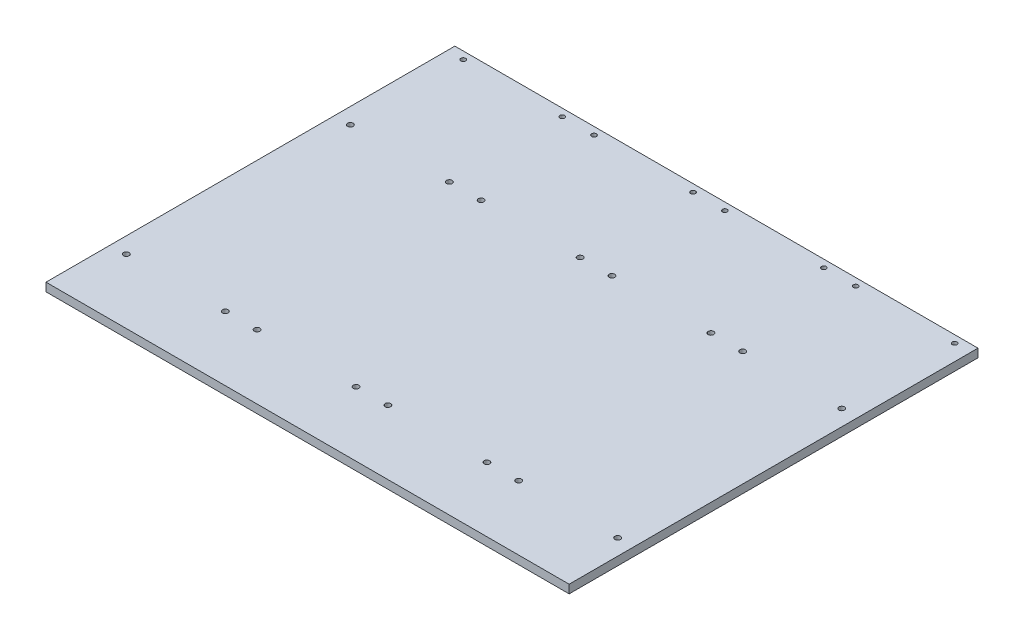
SolidWorks part; units mm, degrees
ref_plane "Front Plane" through (0, 0, 0) normal (0, 0, 1) x (1, 0, 0)
ref_plane "Top Plane" through (0, 0, 0) normal (0, 1, 0) x (1, 0, 0)
ref_plane "Right Plane" through (0, 0, 0) normal (1, 0, 0) x (0, 0, -1)
sketch "Sketch1" plane through (0, 0, 0) normal (0, 1, 0) x (1, 0, 0)
  line L0 (-23.35, 0) -> (23.35, 0) construction
  line L1 (-23.35, 72.9977) -> (23.35, 72.9977)
  line L2 (-23.35, 72.9977) -> (-23.35, -72.9977)
  line L3 (-23.35, -72.9977) -> (23.35, -72.9977)
  line L4 (23.35, 72.9977) -> (23.35, -72.9977)
  line L5 (-23.35, 72.9977) -> (23.35, -72.9977) construction
  line L6 (-23.35, -72.9977) -> (23.35, 72.9977) construction
  line L7 (0, 72.9977) -> (0, -72.9977) construction
  line L8 (-17.675, 72.9977) -> (-17.675, -72.9977) construction
  line L9 (-20.35, 72.9977) -> (-20.35, -72.9977) construction
  line L10 (-15, 72.9977) -> (-15, -72.9977) construction
  line L11 (20.35, 72.9977) -> (20.35, -72.9977) construction
  line L12 (17.675, 72.9977) -> (17.675, -72.9977) construction
  line L13 (15, 72.9977) -> (15, -72.9977) construction
  line L15 (23.35, 72.9977) -> (23.35, -72.9977)
  line L18 (23.35, 72.9977) -> (70.05, 72.9977)
  line L19 (23.35, 72.9977) -> (23.35, -72.9977)
  line L20 (23.35, -72.9977) -> (70.05, -72.9977)
  line L21 (70.05, 72.9977) -> (70.05, -72.9977)
  line L22 (70.05, 72.9977) -> (70.05, -72.9977)
  line L23 (23.35, 0) -> (70.05, 0) construction
  line L24 (23.35, 72.9977) -> (70.05, -72.9977) construction
  line L25 (23.35, -72.9977) -> (70.05, 72.9977) construction
  line L26 (46.7, 72.9977) -> (46.7, -72.9977) construction
  line L27 (29.025, 72.9977) -> (29.025, -72.9977) construction
  line L32 (26.35, 72.9977) -> (26.35, -72.9977) construction
  line L33 (31.7, 72.9977) -> (31.7, -72.9977) construction
  line L34 (67.05, 72.9977) -> (67.05, -72.9977) construction
  line L35 (64.375, 72.9977) -> (64.375, -72.9977) construction
  line L36 (61.7, 72.9977) -> (61.7, -72.9977) construction
  line L37 (23.35, -69.9977) -> (70.05, -69.9977) construction
  line L38 (23.35, 50.0023) -> (70.05, 50.0023) construction
  line L39 (23.35, 52.9977) -> (70.05, 52.9977) construction
  line L40 (26.35, 67.6477) -> (31.7, 67.6477) construction
  line L41 (23.35, 50.0023) -> (23.35, -69.9977) construction
  line L46 (23.35, -9.9977) -> (70.05, -9.9977) construction
  line L47 (70.05, 72.9977) -> (116.75, 72.9977)
  line L48 (70.05, 72.9977) -> (70.05, -72.9977)
  line L49 (70.05, -72.9977) -> (116.75, -72.9977)
  line L50 (116.75, 72.9977) -> (116.75, -72.9977)
  line L51 (116.75, 72.9977) -> (116.75, -72.9977)
  line L52 (70.05, 0) -> (116.75, 0) construction
  line L53 (70.05, 72.9977) -> (116.75, -72.9977) construction
  line L54 (70.05, -72.9977) -> (116.75, 72.9977) construction
  line L55 (93.4, 72.9977) -> (93.4, -72.9977) construction
  line L56 (-23.35, -69.9977) -> (23.35, -69.9977) construction
  line L57 (-23.35, 50.0023) -> (23.35, 50.0023) construction
  line L58 (-23.35, 52.9977) -> (23.35, 52.9977) construction
  line L59 (-20.35, 67.6477) -> (-15, 67.6477) construction
  line L60 (75.725, 72.9977) -> (75.725, -72.9977) construction
  line L61 (73.05, 72.9977) -> (73.05, -72.9977) construction
  line L62 (78.4, 72.9977) -> (78.4, -72.9977) construction
  line L63 (113.75, 72.9977) -> (113.75, -72.9977) construction
  line L64 (-23.35, 50.0023) -> (-23.35, -69.9977) construction
  line L65 (-23.35, -9.9977) -> (23.35, -9.9977) construction
  line L66 (111.075, 72.9977) -> (111.075, -72.9977) construction
  line L67 (108.4, 72.9977) -> (108.4, -72.9977) construction
  line L68 (70.05, -69.9977) -> (116.75, -69.9977) construction
  line L69 (70.05, 50.0023) -> (116.75, 50.0023) construction
  line L70 (70.05, 52.9977) -> (116.75, 52.9977) construction
  line L71 (73.05, 67.6477) -> (78.4, 67.6477) construction
  line L72 (70.05, 50.0023) -> (70.05, -69.9977) construction
  line L73 (70.05, -9.9977) -> (116.75, -9.9977) construction
  line L74 (116.75, 72.9977) -> (163.45, 72.9977)
  line L75 (116.75, 72.9977) -> (116.75, -72.9977)
  line L76 (116.75, -72.9977) -> (163.45, -72.9977)
  line L77 (163.45, 72.9977) -> (163.45, -72.9977)
  line L78 (163.45, 72.9977) -> (163.45, -72.9977)
  line L79 (116.75, 0) -> (163.45, 0) construction
  line L80 (116.75, 72.9977) -> (163.45, -72.9977) construction
  line L81 (116.75, -72.9977) -> (163.45, 72.9977) construction
  line L82 (140.1, 72.9977) -> (140.1, -72.9977) construction
  line L83 (122.425, 72.9977) -> (122.425, -72.9977) construction
  line L84 (119.75, 72.9977) -> (119.75, -72.9977) construction
  line L85 (125.1, 72.9977) -> (125.1, -72.9977) construction
  line L86 (160.45, 72.9977) -> (160.45, -72.9977) construction
  line L87 (157.775, 72.9977) -> (157.775, -72.9977) construction
  line L88 (155.1, 72.9977) -> (155.1, -72.9977) construction
  line L89 (116.75, -69.9977) -> (163.45, -69.9977) construction
  line L90 (116.75, 50.0023) -> (163.45, 50.0023) construction
  line L91 (116.75, 52.9977) -> (163.45, 52.9977) construction
  line L92 (119.75, 67.6477) -> (125.1, 67.6477) construction
  line L93 (116.75, 50.0023) -> (116.75, -69.9977) construction
  line L94 (116.75, -9.9977) -> (163.45, -9.9977) construction
  circle A0 centre (-17.675, 30.0023) radius 1
  circle A3 centre (17.675, 30.0023) radius 1
  circle A16 centre (-17.675, 70.3227) radius 0.85
  circle A21 centre (17.675, -49.9977) radius 1
  circle A22 centre (-17.675, -49.9977) radius 1
  circle A23 centre (17.675, 70.3227) radius 0.85
  circle A24 centre (29.025, 30.0023) radius 1
  circle A25 centre (64.375, 30.0023) radius 1
  circle A26 centre (29.025, 70.3227) radius 0.85
  circle A27 centre (64.375, -49.9977) radius 1
  circle A28 centre (29.025, -49.9977) radius 1
  circle A29 centre (64.375, 70.3227) radius 0.85
  circle A30 centre (75.725, 30.0023) radius 1
  circle A31 centre (111.075, 30.0023) radius 1
  circle A32 centre (75.725, 70.3227) radius 0.85
  circle A33 centre (111.075, -49.9977) radius 1
  circle A34 centre (75.725, -49.9977) radius 1
  circle A35 centre (111.075, 70.3227) radius 0.85
  circle A36 centre (122.425, 30.0023) radius 1
  circle A37 centre (157.775, 30.0023) radius 1
  circle A38 centre (122.425, 70.3227) radius 0.85
  circle A39 centre (157.775, -49.9977) radius 1
  circle A40 centre (122.425, -49.9977) radius 1
  circle A41 centre (157.775, 70.3227) radius 0.85
  point P0 (0, 0)
  point P37 (46.7, 0)
  point P81 (93.4, 0)
  point P134 (140.1, 0)
  dimension "D5" = 2
  dimension "D6" = 80
  dimension "D13" = 1.7
  dimension "D1" = 120
  dimension "D2" = 4
  dimension "D3" = 2.675
  dimension "D4" = 2.675
  dimension "D7" = 30
  dimension "D9" = 3
  dimension "D10" = 2.9954
  dimension "D11" = 20
  dimension "D12" = 5.35
  dimension "D14" = 2.675
extrude "Boss-Extrude1" add sketch "Sketch1" along normal blind 3
